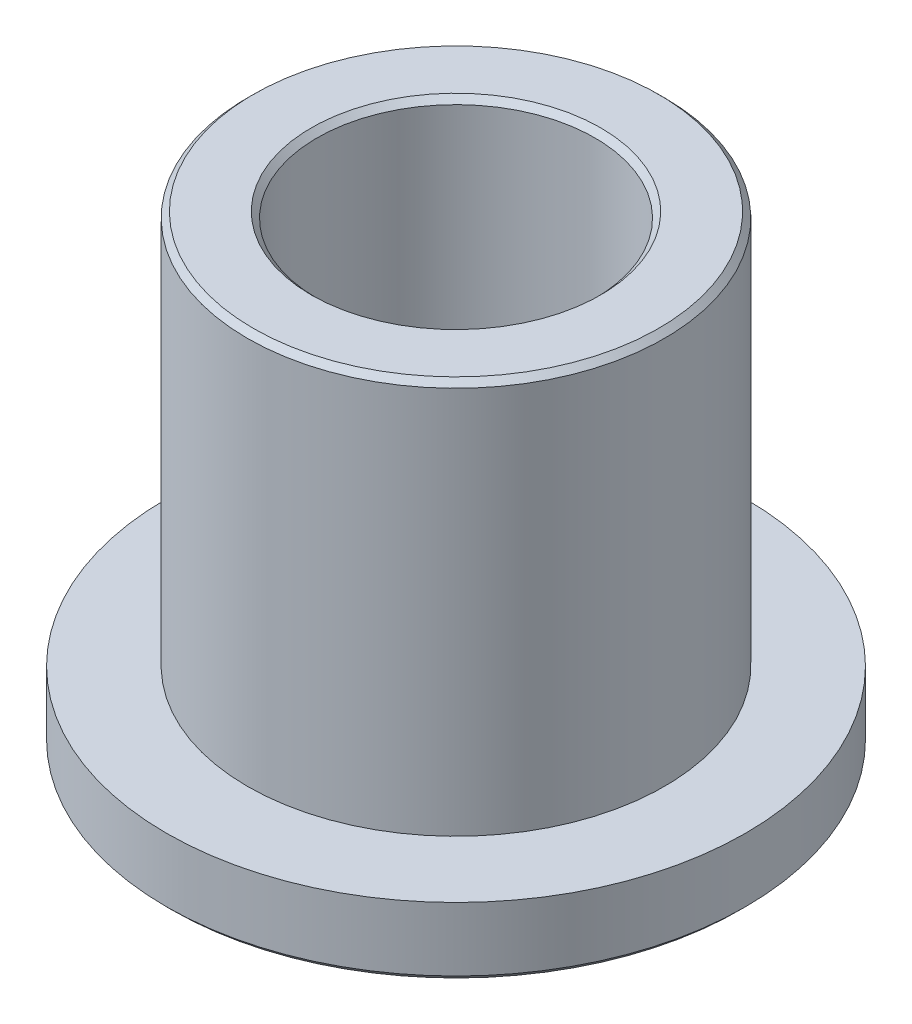
SolidWorks part; units mm, degrees
material "黄铜"
ref_plane "前视基准面" through (0, 0, 0) normal (0, 0, 1) x (1, 0, 0)
ref_plane "上视基准面" through (0, 0, 0) normal (0, 1, 0) x (1, 0, 0)
ref_plane "右视基准面" through (0, 0, 0) normal (1, 0, 0) x (0, 0, -1)
sketch "草图1" plane through (0, 0, 0) normal (0, 1, 0) x (1, 0, 0)
  circle A0 centre (0, 0) radius 12.5
  circle A1 centre (0, 0) radius 6
extrude "凸台-拉伸1" add sketch "草图1" along normal blind 3
sketch "草图2" plane through (0, 3, 0) normal (0, 1, 0) x (1, 0, 0)
  circle A0 centre (0, 0) radius 6 construction
  circle A1 centre (0, 0) radius 6
  circle A2 centre (0, 0) radius 9
extrude "凸台-拉伸2" add sketch "草图2" along normal blind 17
chamfer "倒角1" distance 0.25 angle 45 4 edges at (0, 0, 6) (0, 0, 12.5) (0, 20, 6) (0, 20, 9)
